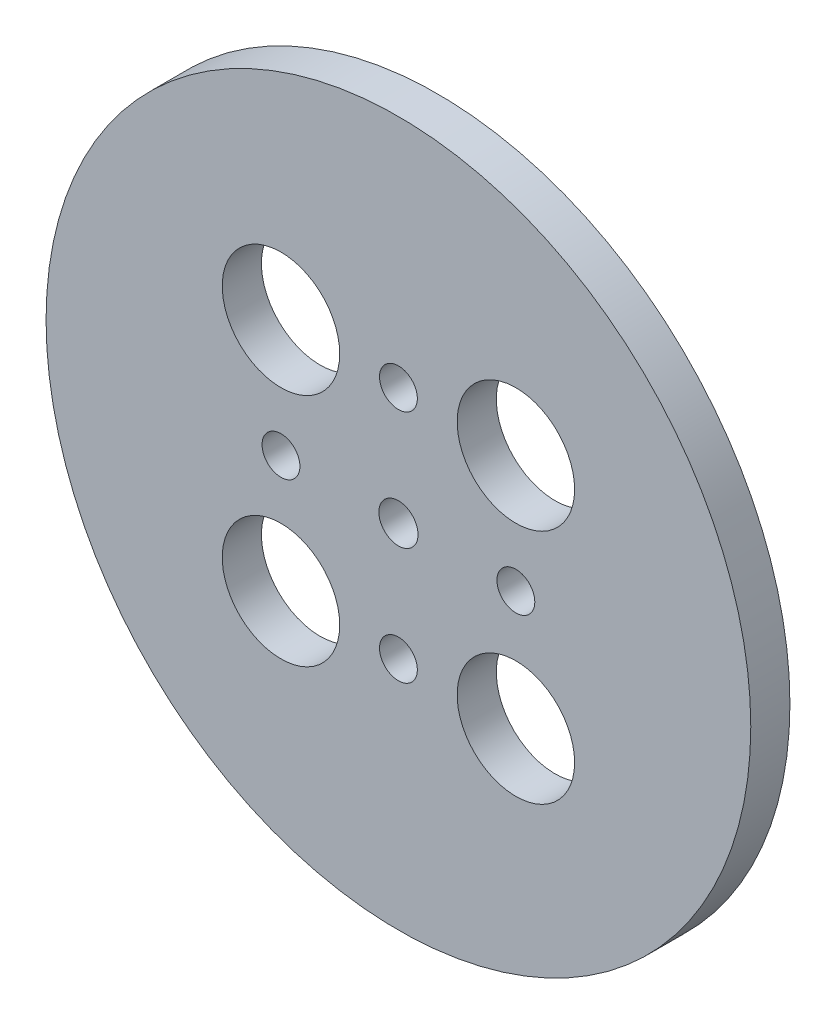
SolidWorks part; units mm, degrees
ref_plane "Alzado" through (0, 0, 0) normal (0, 0, 1) x (1, 0, 0)
ref_plane "Planta" through (0, 0, 0) normal (0, 1, 0) x (1, 0, 0)
ref_plane "Vista lateral" through (0, 0, 0) normal (1, 0, 0) x (0, 0, -1)
sketch "Model" plane through (0, 0, 0) normal (0, 0, 1) x (1, 0, 0)
  circle A0 centre (206.7478, 250.952) radius 4.5
  circle A1 centre (206.7478, 232.952) radius 4.5
  circle A2 centre (224.7478, 232.8274) radius 4.5
  circle A3 centre (224.7478, 250.952) radius 4.5
  circle A4 centre (215.7478, 241.952) radius 1.5
  circle A5 centre (215.7478, 232.952) radius 1.45
  circle A6 centre (215.7478, 250.952) radius 1.45
  circle A7 centre (224.7478, 241.952) radius 1.45
  circle A8 centre (206.7478, 241.952) radius 1.45
  circle A9 centre (215.7478, 241.952) radius 27
extrude "Saliente-Extruir1" add sketch "Model" along normal blind 3
